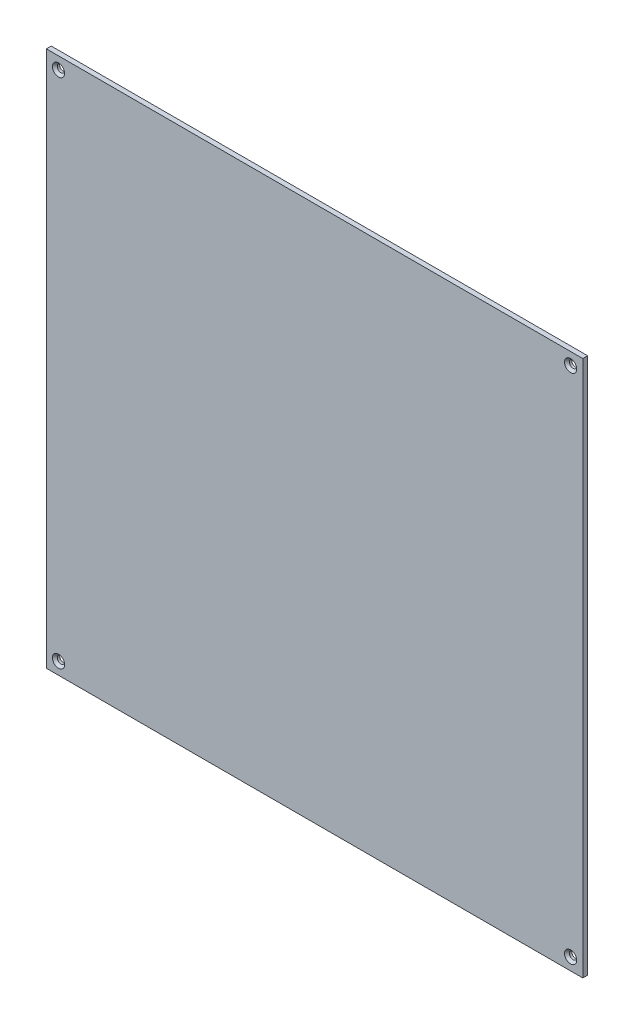
SolidWorks part; units mm, degrees
ref_plane "Front Plane" through (0, 0, 0) normal (0, 0, 1) x (1, 0, 0)
ref_plane "Top Plane" through (0, 0, 0) normal (0, 1, 0) x (1, 0, 0)
ref_plane "Right Plane" through (0, 0, 0) normal (1, 0, 0) x (0, 0, -1)
sketch "Sketch1" plane through (0, 0, 0) normal (0, 0, 1) x (1, 0, 0)
  line L0 (-105, -105) -> (105, -105) construction
  line L1 (-110, 110) -> (110, 110)
  line L2 (-110, 110) -> (-110, -110)
  line L3 (-110, -110) -> (110, -110)
  line L4 (110, 110) -> (110, -110)
  line L5 (-110, 110) -> (110, -110) construction
  line L6 (-110, -110) -> (110, 110) construction
  line L7 (105, -105) -> (105, 105) construction
  line L8 (105, 105) -> (-105, 105) construction
  line L9 (-105, 105) -> (-105, -105) construction
  circle A0 centre (-105, 105) radius 1.5
  circle A1 centre (105, 105) radius 1.5
  circle A2 centre (105, -105) radius 1.5
  circle A3 centre (-105, -105) radius 1.5
  point P0 (0, 0)
  dimension "D2" = 3
  dimension "D1" = 220
  dimension "D3" = 5
extrude "Boss-Extrude1" add sketch "Sketch1" along normal blind 2
chamfer "Chamfer1" distance 1 angle 45 4 edges at (-103.5, 105, 2) (106.5, 105, 2) (106.5, -105, 2) (-103.5, -105, 2)
